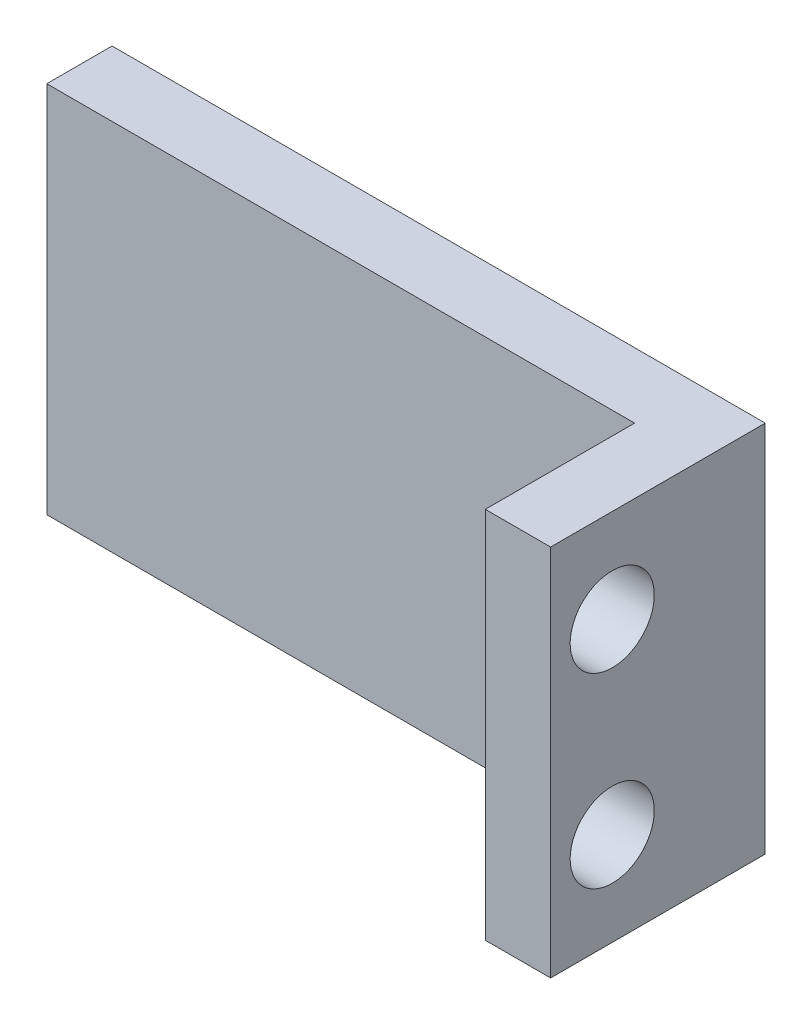
SolidWorks part; units mm, degrees
ref_plane "前视基准面" through (0, 0, 0) normal (0, 0, 1) x (1, 0, 0)
ref_plane "上视基准面" through (0, 0, 0) normal (0, 1, 0) x (1, 0, 0)
ref_plane "右视基准面" through (0, 0, 0) normal (1, 0, 0) x (0, 0, -1)
sketch "草图1" plane through (0, 0, 0) normal (0, 0, 1) x (1, 0, 0)
  line L1 (17.5, -10) -> (-17.5, -10)
  line L2 (17.5, -10) -> (17.5, 10)
  line L3 (17.5, 10) -> (-17.5, 10)
  line L4 (-17.5, -10) -> (-17.5, 10)
  line L5 (17.5, -10) -> (-17.5, 10) construction
  line L6 (17.5, 10) -> (-17.5, -10) construction
  point P0 (0, 0)
  dimension "D1" = 20
  dimension "D2" = 35
extrude "凸台-拉伸1" add sketch "草图1" along normal blind 3.5
sketch "草图2" plane through (0, 0, 3.5) normal (0, 0, 1) x (1, 0, 0)
  line L0 (17.5, 10) -> (-17.5, 10) construction
  line L1 (17.5, -10) -> (14, -10)
  line L2 (17.5, -10) -> (17.5, 10)
  line L3 (17.5, 10) -> (14, 10)
  line L4 (14, -10) -> (14, 10)
  dimension "D1" = 3.5
extrude "凸台-拉伸2" add sketch "草图2" along normal blind 8
sketch "草图3" plane through (14, 0, 0) normal (-1, 0, 0) x (0, 0, 1)
  line L0 (3.5, 0) -> (8.2, 0) construction
  line L1 (3.5, 10) -> (3.5, -10) construction
  line L2 (8.2, 0) -> (8.2, 5) construction
  circle A0 centre (8.2, 5) radius 2.255
  circle A1 centre (8.2, -5) radius 2.255
  dimension "D1" = 4.51
  dimension "D2" = 4.7
  dimension "D3" = 5
extrude "切除-拉伸1" cut sketch "草图3" against normal blind 8
